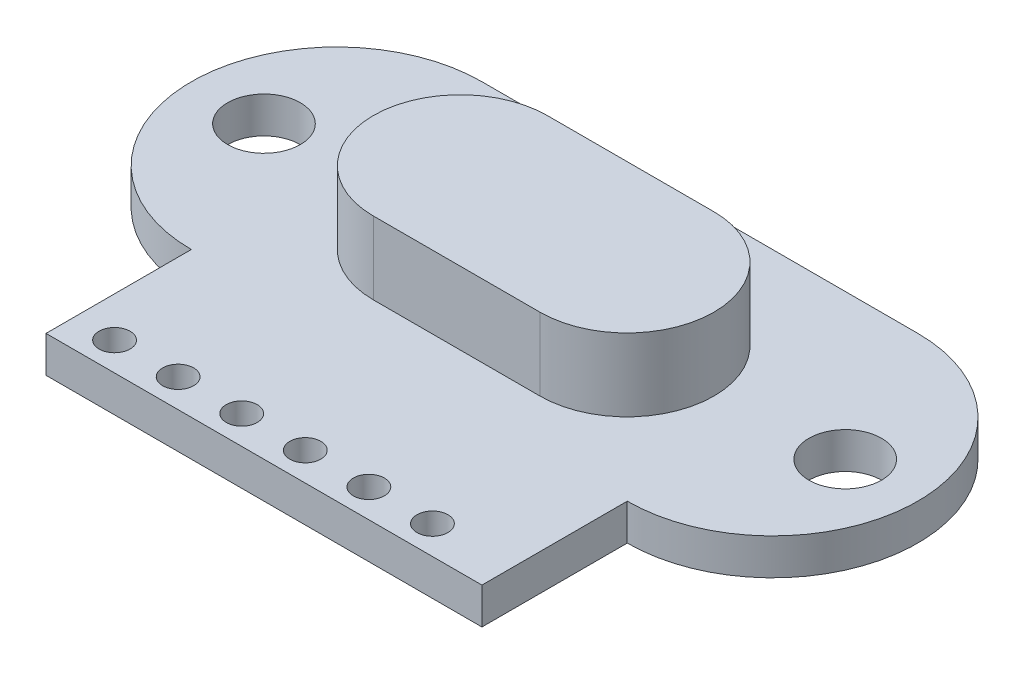
SolidWorks part; units mm, degrees
ref_plane "Front Plane" through (0, 0, 0) normal (0, 0, 1) x (1, 0, 0)
ref_plane "Top Plane" through (0, 0, 0) normal (0, 1, 0) x (1, 0, 0)
ref_plane "Right Plane" through (0, 0, 0) normal (1, 0, 0) x (0, 0, -1)
sketch "Sketch1" plane through (0, 0, 0) normal (0, 1, 0) x (1, 0, 0)
  line L0 (-6, 8) -> (6, 8) construction
  line L1 (-6, 12) -> (6, 12)
  line L2 (-6, 4) -> (6, 4)
  line L3 (0, 8) -> (0, 0) construction
  arc A0 (-6, 12) -> (-6, 4) centre (-6, 8) ccw
  arc A1 (6, 4) -> (6, 12) centre (6, 8) ccw
  point P2 (0, 8)
  dimension "D2" = 20
  dimension "D1" = 12
  dimension "D3" = 8
extrude "Boss-Extrude1" add sketch "Sketch1" along normal blind 1
sketch "Sketch2" plane through (0, 0, 0) normal (0, -1, 0) x (1, 0, 0)
  line L1 (-6, -4) -> (6, -4)
  line L2 (-6, -4) -> (-6, 0)
  line L3 (-6, 0) -> (6, 0)
  line L4 (6, -4) -> (6, 0)
extrude "Boss-Extrude2" add sketch "Sketch2" against normal blind 1
sketch "Sketch3" plane through (0, 1, 0) normal (0, 1, 0) x (1, 0, 0)
  line L0 (-8, 8) -> (8, 8) construction
  line L1 (0, 4) -> (0, 8) construction
  line L2 (-6, 4) -> (6, 4) construction
  circle A0 centre (8, 8) radius 1
  circle A1 centre (-8, 8) radius 1
  circle A2 centre (-4.8957, 0.7833) radius 0.4268
  circle A8 centre (-3.1457, 0.7833) radius 0.4268
  circle A9 centre (-1.3957, 0.7833) radius 0.4268
  circle A10 centre (0.3543, 0.7833) radius 0.4268
  circle A11 centre (2.1043, 0.7833) radius 0.4268
  circle A12 centre (3.8543, 0.7833) radius 0.4268
  dimension "D1" = 2
  dimension "D4" = 6
  dimension "D2" = 4
  dimension "D3" = 16
extrude "Cut-Extrude1" cut sketch "Sketch3" against normal through all
sketch "Sketch4" plane through (0, 1, 0) normal (0, 1, 0) x (1, 0, 0)
  line L0 (-2.294, 7.6988) -> (2.294, 7.6988) construction
  line L1 (-2.294, 10.0931) -> (2.294, 10.0931)
  line L2 (-2.294, 5.3044) -> (2.294, 5.3044)
  line L3 (0, 7.6988) -> (0, 0) construction
  arc A0 (-2.294, 10.0931) -> (-2.294, 5.3044) centre (-2.294, 7.6988) ccw
  arc A1 (2.294, 5.3044) -> (2.294, 10.0931) centre (2.294, 7.6988) ccw
  point P2 (0, 7.6988)
extrude "Boss-Extrude3" add sketch "Sketch4" along normal blind 2
sketch "Sketch5" plane through (0, 0, 0) normal (0, -1, 0) x (1, 0, 0)
  line L1 (-4.4007, -4.2879) -> (4.1466, -4.2879)
  line L2 (-4.4007, -4.2879) -> (-4.4007, -9.6116)
  line L3 (-4.4007, -9.6116) -> (4.1466, -9.6116)
  line L4 (4.1466, -4.2879) -> (4.1466, -9.6116)
extrude "Boss-Extrude4" add sketch "Sketch5" along normal blind 1
